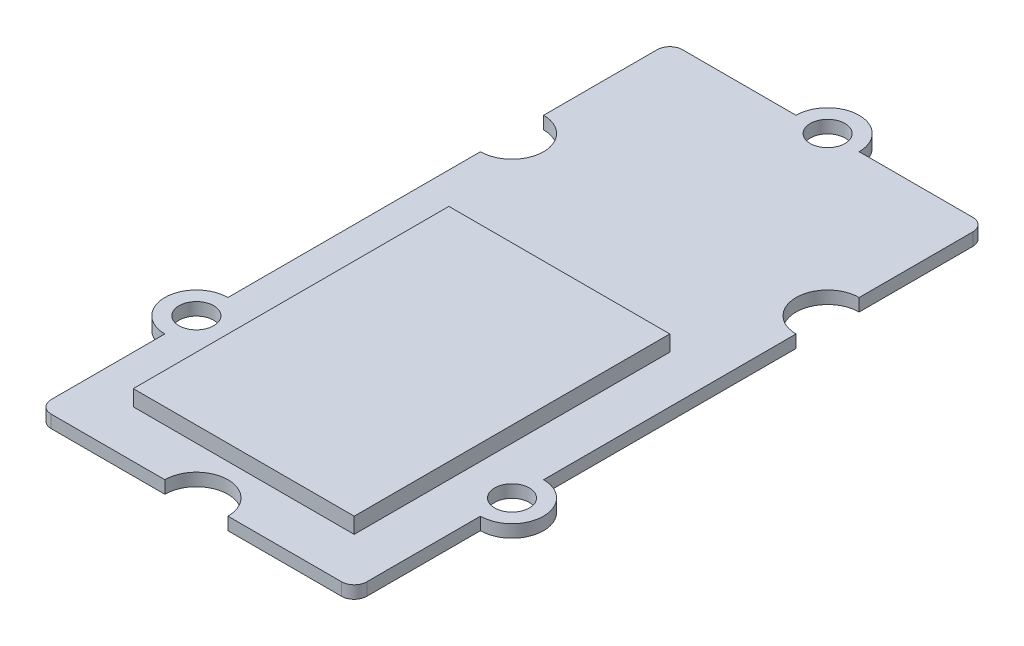
SolidWorks part; units mm, degrees
ref_plane "Front Plane" through (0, 0, 0) normal (0, 0, 1) x (1, 0, 0)
ref_plane "Top Plane" through (0, 0, 0) normal (0, 1, 0) x (1, 0, 0)
ref_plane "Right Plane" through (0, 0, 0) normal (1, 0, 0) x (0, 0, -1)
sketch "Sketch1" plane through (0, 0, 0) normal (0, 1, 0) x (1, 0, 0)
  line L0 (10, 0) -> (10, 40) construction
  line L1 (0.8, 0) -> (8, 0)
  line L2 (0, 0.8) -> (0, 8)
  line L3 (0.8, 40) -> (8, 40)
  line L4 (20, 0.8) -> (20, 8)
  line L5 (12, 40) -> (19.2, 40)
  line L6 (0, 32) -> (0, 39.2)
  line L7 (20, 32) -> (20, 39.2)
  line L8 (0, 12) -> (0, 28)
  line L9 (20, 12) -> (20, 28)
  line L10 (12, 0) -> (19.2, 0)
  arc A0 (0.8, 0) -> (0, 0.8) centre (0.8, 0.8) cw
  arc A1 (19.2, 0) -> (20, 0.8) centre (19.2, 0.8) ccw
  arc A2 (19.2, 40) -> (20, 39.2) centre (19.2, 39.2) cw
  arc A3 (0, 39.2) -> (0.8, 40) centre (0.8, 39.2) cw
  arc A4 (12, 40) -> (8, 40) centre (10, 40) ccw
  circle A5 centre (10, 40) radius 1.1
  arc A6 (0, 28) -> (0, 32) centre (0, 30) ccw
  arc A7 (20, 32) -> (20, 28) centre (20, 30) ccw
  arc A8 (0, 12) -> (0, 8) centre (0, 10) ccw
  arc A9 (20, 8) -> (20, 12) centre (20, 10) ccw
  arc A10 (12, 0) -> (8, 0) centre (10, 0) ccw
  circle A11 centre (0, 10) radius 1.1
  circle A12 centre (20, 10) radius 1.1
  point P7 (0, 0)
  point P10 (20, 0)
  point P13 (20, 40)
  dimension "D3" = 0.8
  dimension "D4" = 2
  dimension "D5" = 2.2
  dimension "D1" = 20
  dimension "D2" = 40
  dimension "D6" = 10
  dimension "D7" = 30
  dimension "D8" = 30
extrude "Board" add sketch "Sketch1" along normal blind 0.8
sketch "Esquisse1" plane through (0, 0.8, 0) normal (0, 1, 0) x (1, 0, 0)
  line L0 (0, 28) -> (0, 12) construction
  line L1 (3, 23) -> (17, 23)
  line L2 (3, 23) -> (3, 3)
  line L3 (3, 3) -> (17, 3)
  line L4 (17, 23) -> (17, 3)
  line L5 (20, 12) -> (20, 28) construction
  line L6 (12, 0) -> (19.2, 0) construction
  dimension "D1" = 3
  dimension "D2" = 3
  dimension "D3" = 3
  dimension "D4" = 5
extrude "Capteurs" add sketch "Esquisse1" along normal blind 1
